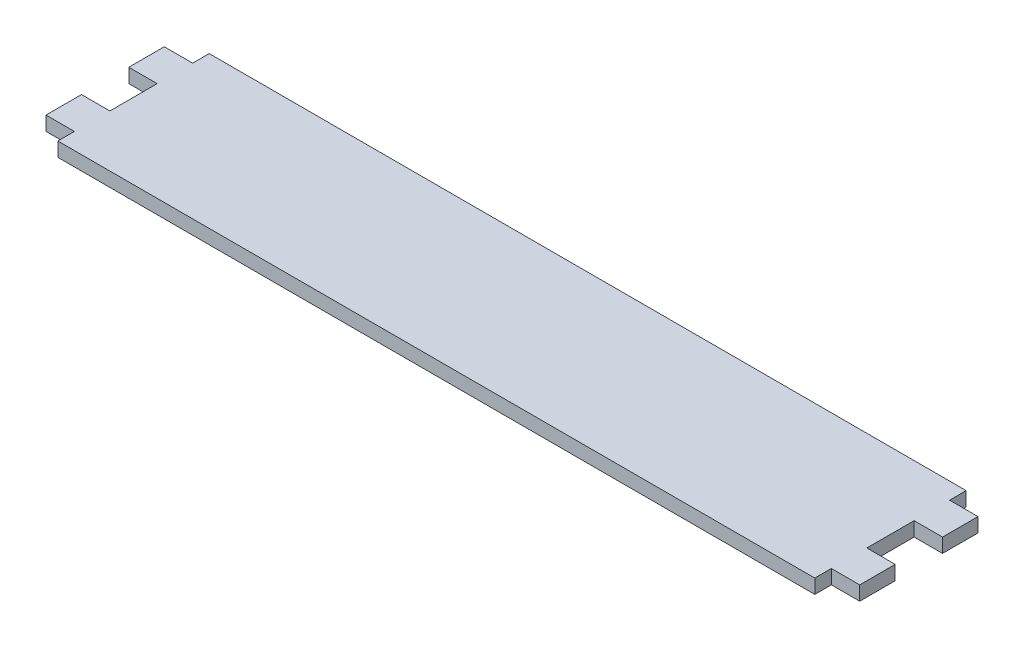
SolidWorks part; units mm, degrees
ref_plane "Front" through (0, 0, 0) normal (0, 0, 1) x (1, 0, 0)
ref_plane "Top" through (0, 0, 0) normal (0, 1, 0) x (1, 0, 0)
ref_plane "Right" through (0, 0, 0) normal (1, 0, 0) x (0, 0, -1)
sketch "Skizze1" plane through (0, 0, 0) normal (0, 1, 0) x (1, 0, 0)
  line L1 (160, 32) -> (-160, 32)
  line L2 (160, 32) -> (160, -32)
  line L3 (160, -32) -> (-160, -32)
  line L4 (-160, 32) -> (-160, -32)
  line L5 (160, 32) -> (-160, -32) construction
  line L6 (160, -32) -> (-160, 32) construction
  point P0 (0, 0)
  dimension "D1" = 320
  dimension "D2" = 64
extrude "Grundform" add sketch "Skizze1" along normal blind 6
sketch "Skizze2" plane through (0, 6, 0) normal (0, 1, 0) x (1, 0, 0)
  line L0 (0, 32) -> (0, 14) construction
  line L1 (160, 32) -> (-160, 32) construction
  line L2 (0, 14) -> (0, -14) construction
  line L3 (0, -14) -> (0, -32) construction
  line L4 (-160, -32) -> (160, -32) construction
  line L5 (0, -14) -> (-31, -14) construction
  line L6 (-31, -14) -> (-62, -14) construction
  line L7 (-62, -14) -> (-93, -14) construction
  line L8 (-93, -14) -> (-124, -14) construction
  line L10 (-15.5, 14) -> (-15.5, -14) construction
  line L11 (-15.5, 14) -> (0, 14) construction
  line L12 (-15.5, 14) -> (-46.5, 14) construction
  line L13 (-46.5, 14) -> (-77.5, 14) construction
  line L14 (-77.5, 14) -> (-108.5, 14) construction
  line L15 (-108.5, 14) -> (-139.5, 14) construction
  circle A0 centre (0, -14) radius 13.25
  circle A1 centre (-31, -14) radius 13.25
  circle A2 centre (-62, -14) radius 13.25
  circle A3 centre (-93, -14) radius 13.25
  circle A4 centre (-124, -14) radius 13.25
  circle A6 centre (-15.5, 14) radius 13.25
  circle A7 centre (-46.5, 14) radius 13.25
  circle A8 centre (-77.5, 14) radius 13.25
  circle A9 centre (-108.5, 14) radius 13.25
  circle A10 centre (-139.5, 14) radius 13.25
  circle A12 centre (124, -14) radius 13.25
  circle A13 centre (93, -14) radius 13.25
  circle A14 centre (62, -14) radius 13.25
  circle A15 centre (31, -14) radius 13.25
  circle A16 centre (139.5, 14) radius 13.25
  circle A17 centre (108.5, 14) radius 13.25
  circle A18 centre (77.5, 14) radius 13.25
  circle A19 centre (46.5, 14) radius 13.25
  circle A20 centre (15.5, 14) radius 13.25
  dimension "D1" = 26.5
  dimension "D2" = 18
  dimension "D3" = 31
extrude "Flaschendurchbruch" [suppressed] cut sketch "Skizze2" against normal through all
ref_plane "Ebene1" through (0, 0, 0) normal (1, 0, 0) x (0, 0, -1)
sketch "Skizze3" plane through (-160, 0, 0) normal (-1, 0, 0) x (0, 0, 1)
  line L0 (-32, 6) -> (32, 6) construction
  line L1 (-25, 6) -> (-10, 6)
  line L2 (-25, 6) -> (-25, 0)
  line L3 (-25, 0) -> (-10, 0)
  line L4 (-10, 6) -> (-10, 0)
  line L5 (-32, 0) -> (32, 0) construction
  line L6 (0, 0) -> (0, 6) construction
  line L11 (10, 6) -> (10, 0)
  line L12 (25, 0) -> (10, 0)
  line L13 (25, 6) -> (25, 0)
  line L14 (25, 6) -> (10, 6)
  dimension "D1" = 20
  dimension "D2" = 15
extrude "Aufsatz-Linear austragen2" add sketch "Skizze3" along normal blind 12
mirror "Spiegeln1" about plane through (0, 0, 0) normal (1, 0, 0) of "Aufsatz-Linear austragen2"
